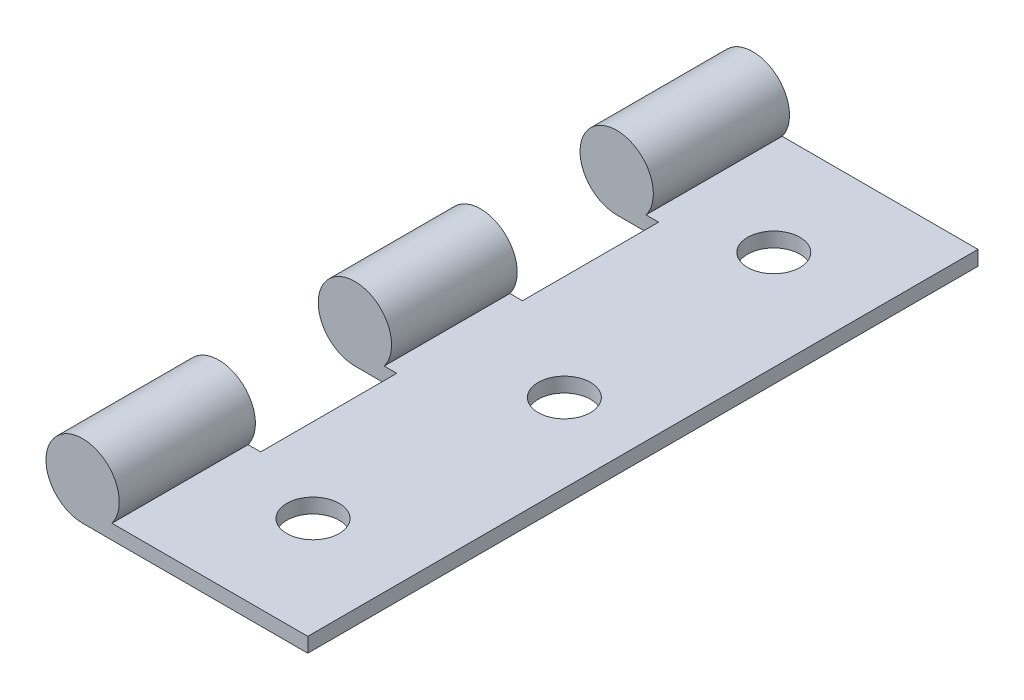
SolidWorks part; units mm, degrees
ref_plane "Front Plane" through (0, 0, 0) normal (0, 0, 1) x (1, 0, 0)
ref_plane "Top Plane" through (0, 0, 0) normal (0, 1, 0) x (1, 0, 0)
ref_plane "Right Plane" through (0, 0, 0) normal (1, 0, 0) x (0, 0, -1)
sketch "Sketch1" plane through (0, 0, 0) normal (0, 0, 1) x (1, 0, 0)
  line L1 (0, 0) -> (21.5, 0)
  line L3 (2.8, 1.4) -> (21.5, 1.4)
  line L4 (21.5, 0) -> (21.5, 1.4)
  arc A0 (2.8, 1.4) -> (0, 0) centre (0, 3.5) ccw
  dimension "D1" = 7
  dimension "D2" = 21.5
  dimension "D3" = 1.4
extrude "Boss-Extrude1" add sketch "Sketch1" along normal blind 64
sketch "Sketch2" plane through (0, 0, 0) normal (0, 1, 0) x (1, 0, 0)
  circle A0 centre (12, -54) radius 2.5
  circle A1 centre (14, -32) radius 2.5
  circle A2 centre (12, -10) radius 2.5
  dimension "D1" = 5
  dimension "D2" = 5
  dimension "D3" = 5
  dimension "D4" = 12
  dimension "D5" = 10
  dimension "D6" = 44
  dimension "D7" = 22
  dimension "D8" = 2
extrude "Cut-Extrude2" cut sketch "Sketch2" along normal blind 5
sketch "Sketch3" plane through (0, 0, 0) normal (0, 1, 0) x (1, 0, 0)
  line L0 (-4, -26) -> (-4, -13)
  line L3 (-4, -13) -> (4, -13)
  line L5 (-4, -26) -> (4, -26)
  line L7 (-4, -38) -> (4, -38)
  line L9 (-4, -51) -> (4, -51)
  line L13 (4, -26) -> (4, -13)
  line L14 (4, -38) -> (4, -51)
  line L15 (-4, -51) -> (-4, -38)
  dimension "D1" = 13
  dimension "D2" = 4
  dimension "D4" = 8
  dimension "D5" = 8
  dimension "D6" = 13
  dimension "D7" = 12
  dimension "D8" = 13
extrude "Cut-Extrude3" cut sketch "Sketch3" along normal blind 15
